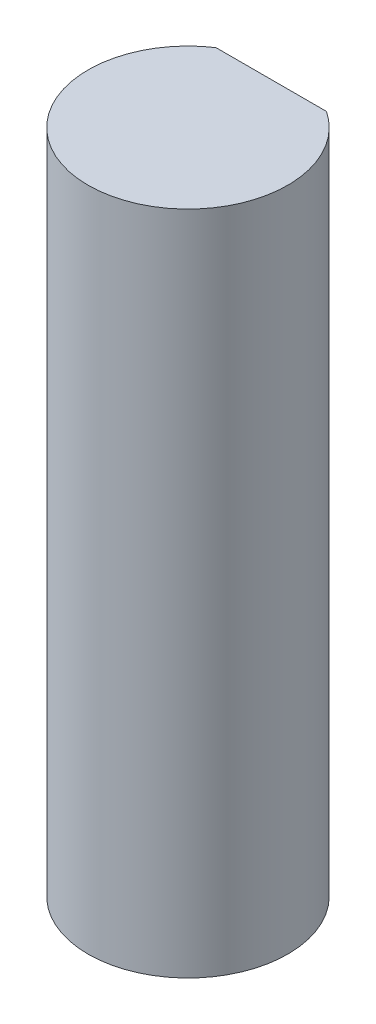
SolidWorks part; units mm, degrees
material "Plain Carbon Steel"
ref_plane "Front Plane" through (0, 0, 0) normal (0, 0, 1) x (1, 0, 0)
ref_plane "Top Plane" through (0, 0, 0) normal (0, 1, 0) x (1, 0, 0)
ref_plane "Right Plane" through (0, 0, 0) normal (1, 0, 0) x (0, 0, -1)
sketch "Sketch1" plane through (0, 0, 0) normal (0, 1, 0) x (1, 0, 0)
  circle A0 centre (0, 0) radius 3
  dimension "D1" = 6
extrude "Boss-Extrude1" add sketch "Sketch1" along normal blind 20
sketch "Sketch2" plane through (0, 20, 0) normal (0, 1, 0) x (1, 0, 0)
  line L1 (-1.6583, 2.5) -> (3, 2.5)
  line L2 (-1.6583, 2.5) -> (-1.6583, 10.3388)
  line L3 (-1.6583, 10.3388) -> (3, 10.3388)
  line L4 (3, 2.5) -> (3, 10.3388)
  circle A0 centre (0, 0) radius 3 construction
  dimension "D1" = 2.5
extrude "Cut-Extrude1" cut sketch "Sketch2" against normal blind 14
